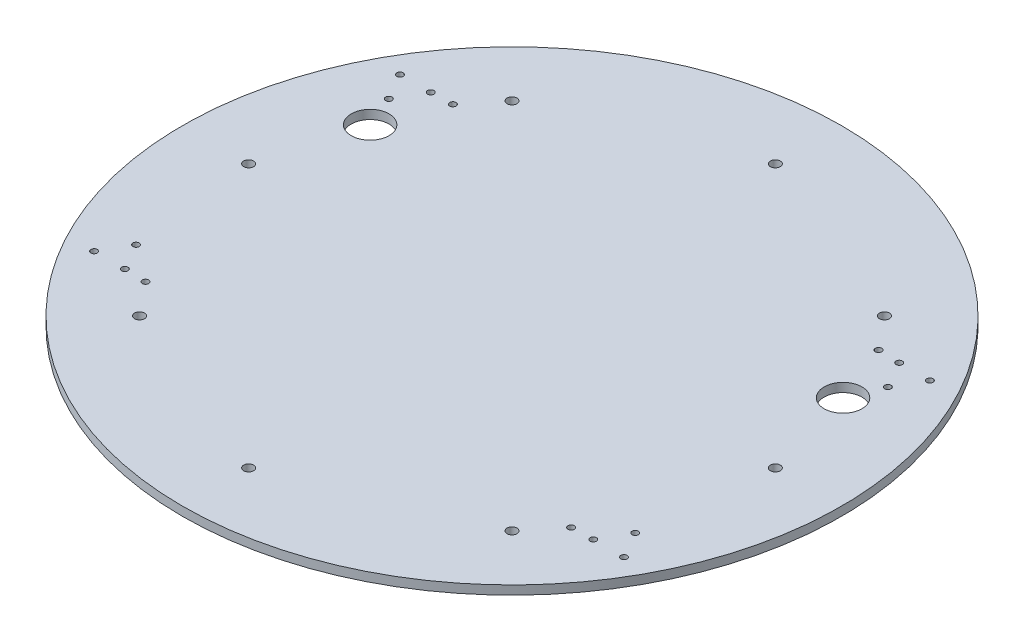
SolidWorks part; units mm, degrees
ref_plane "Front Plane" through (0, 0, 0) normal (0, 0, 1) x (1, 0, 0)
ref_plane "Top Plane" through (0, 0, 0) normal (0, 1, 0) x (1, 0, 0)
ref_plane "Right Plane" through (0, 0, 0) normal (1, 0, 0) x (0, 0, -1)
sketch "Sketch1" plane through (0, 0, 0) normal (0, 1, 0) x (1, 0, 0)
  circle A0 centre (0, 0) radius 177
  dimension "D1" = 354
extrude "Boss-Extrude1" add sketch "Sketch1" along normal blind 4.7625
sketch "Sketch3" plane through (0, 4.7625, 0) normal (0, 1, 0) x (1, 0, 0)
  line L0 (-188.2869, 0) -> (208.0556, 0) construction
  line L1 (0, 177) -> (0, -177) construction
  circle A1 centre (-114.3, -82.55) radius 1.7
  circle A2 centre (-114.3, 82.55) radius 1.7
  circle A3 centre (114.3, 82.55) radius 1.7
  circle A4 centre (114.3, -82.55) radius 1.7
  circle A5 centre (0, 0) radius 177 construction
  dimension "D2" = 3.4
  dimension "D3" = 3.4
  dimension "D4" = 3.4
  dimension "D5" = 3.4
  dimension "D6" = 82.55
  dimension "D7" = 82.55
  dimension "D8" = 82.55
  dimension "D9" = 82.55
  dimension "D10" = 114.3
  dimension "D11" = 114.3
  dimension "D12" = 114.3
  dimension "D13" = 114.3
extrude "Cut-Extrude1" cut sketch "Sketch3" against normal blind 2.54
sketch "Sketch4" plane through (0, 4.7625, 0) normal (0, 1, 0) x (1, 0, 0)
  line L0 (-177, 0) -> (177, 0) construction
  line L1 (0, 177) -> (0, -177) construction
  circle A16 centre (0, 0) radius 177 construction
  circle A36 centre (142.288, -82.15) radius 1.7
  circle A37 centre (125.7902, -82.15) radius 1.7
  circle A38 centre (134.0391, -67.8625) radius 1.7
  circle A39 centre (-134.0391, -67.8625) radius 1.7
  circle A40 centre (-125.7902, -82.15) radius 1.7
  circle A41 centre (-142.288, -82.15) radius 1.7
  circle A42 centre (-142.288, 82.15) radius 1.7
  circle A43 centre (-125.7902, 82.15) radius 1.7
  circle A44 centre (-134.0391, 67.8625) radius 1.7
  circle A45 centre (134.0391, 67.8625) radius 1.7
  circle A46 centre (125.7902, 82.15) radius 1.7
  circle A47 centre (142.288, 82.15) radius 1.7
  point P15 (134.0391, -77.3875)
  point P19 (-134.0391, -77.3875)
  dimension "D2" = 3.4
  dimension "D5" = 3
extrude "Cut-Extrude2" cut sketch "Sketch4" against normal through all
sketch "Sketch5" plane through (0, 4.7625, 0) normal (0, 1, 0) x (1, 0, 0)
  circle A0 centre (-127, 50.8) radius 10.16
  circle A1 centre (127, 50.8) radius 10.16
  point P5 (96.3825, 50.8)
  dimension "D1" = 20.32
  dimension "D3" = 50.8
  dimension "D2" = 127
  dimension "D4" = 127
  dimension "D5" = 50.8
extrude "Wires" cut sketch "Sketch5" against normal through all
sketch "Sketch6" plane through (0, 4.7625, 0) normal (0, 1, 0) x (1, 0, 0)
  line L0 (0, 177) -> (0, -177) construction
  circle A0 centre (0, -141.44) radius 2.667
  circle A1 centre (0, 0) radius 177 construction
  circle A2 centre (-100.0132, -100.0132) radius 2.667
  circle A3 centre (-141.44, 0) radius 2.667
  circle A4 centre (-100.0132, 100.0132) radius 2.667
  circle A5 centre (0, 141.44) radius 2.667
  circle A6 centre (100.0132, 100.0132) radius 2.667
  circle A7 centre (141.44, 0) radius 2.667
  circle A8 centre (100.0132, -100.0132) radius 2.667
  point P23 (0, 0)
  dimension "D1" = 35.56
  dimension "D2" = 5.334
  dimension "D3" = 8
extrude "Zip Ties" cut sketch "Sketch6" against normal through all
